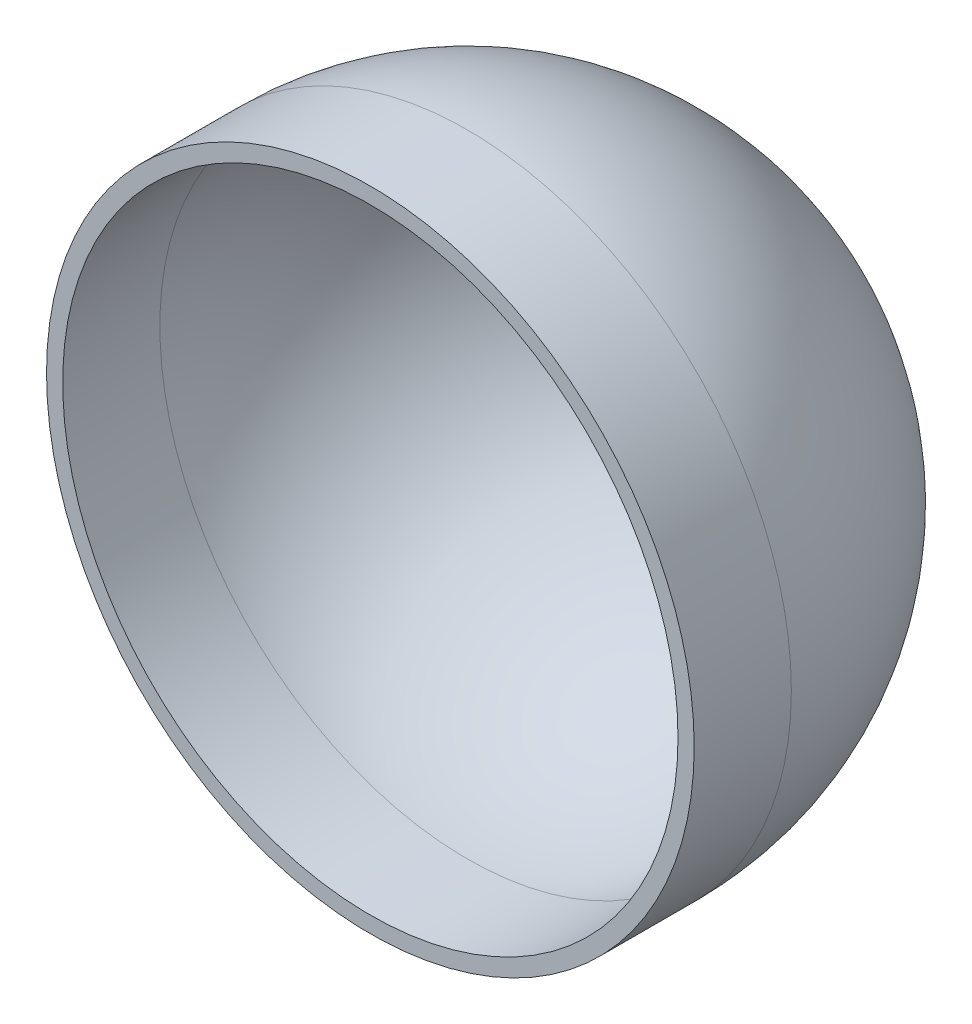
SolidWorks part; units mm, degrees
material "ABS PC"
ref_plane "前视" through (0, 0, 0) normal (0, 0, 1) x (1, 0, 0)
ref_plane "上视" through (0, 0, 0) normal (0, 1, 0) x (1, 0, 0)
ref_plane "右视" through (0, 0, 0) normal (1, 0, 0) x (0, 0, -1)
sketch "草图2" plane through (0, 0, 0) normal (0, 1, 0) x (1, 0, 0)
  line L0 (100, 0) -> (95, 0)
  line L1 (0, 100) -> (0, 95)
  line L2 (0, 95) -> (0, 137.4552) construction
  arc A0 (100, 0) -> (0, 100) centre (0, 0) ccw
  arc A1 (95, 0) -> (0, 95) centre (0, 0) ccw
  dimension "D1" = 5
revolve "旋转1" add sketch "草图2" angle 360 about L2
sketch "草图4" plane through (0, 0, 0) normal (0, 0, 1) x (1, 0, 0)
  circle A0 centre (0, 0) radius 100
  circle A1 centre (0, 0) radius 95
  dimension "D1" = 5
extrude "凸台-拉伸1" add sketch "草图4" along normal blind 30
